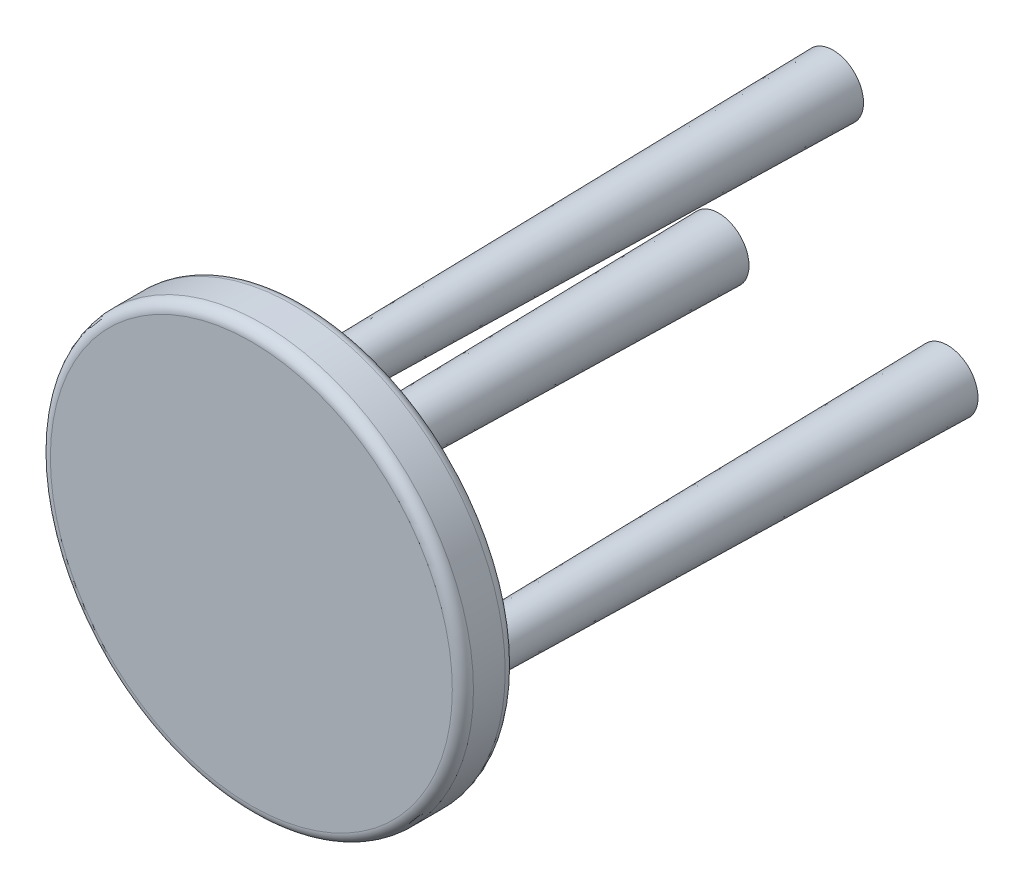
SolidWorks part; units mm, degrees
ref_plane "Front Plane" through (0, 0, 0) normal (0, 0, 1) x (1, 0, 0)
ref_plane "Top Plane" through (0, 0, 0) normal (0, 1, 0) x (1, 0, 0)
ref_plane "Right Plane" through (0, 0, 0) normal (1, 0, 0) x (0, 0, -1)
sketch "Sketch1" plane through (0, 0, 0) normal (0, 0, 1) x (1, 0, 0)
  circle A0 centre (0, 0) radius 40
  dimension "D1" = 80
extrude "Boss-Extrude1" add sketch "Sketch1" along normal blind 10
sketch "Sketch2" plane through (0, 0, 0) normal (0, 0, 1) x (1, 0, 0)
  circle A0 centre (0, 25) radius 4
  circle A1 centre (21.6506, -12.5) radius 4
  circle A2 centre (-21.6506, -12.5) radius 4
  point P9 (0, 0)
  dimension "D2" = 8
  dimension "D3" = 25
  dimension "D1" = 3
extrude "Boss-Extrude2" add sketch "Sketch2" against normal blind 100 draft 1 draft outward yes
fillet "Fillet1" radius 2 1 edges at (40, 0, 10)
fillet "Fillet2" radius 2 1 edges at (40, 0, 0)
fillet "Fillet3" radius 4 3 edges at (4, 25, 0) (-17.6506, -12.5, 0) (25.6506, -12.5, 0)
